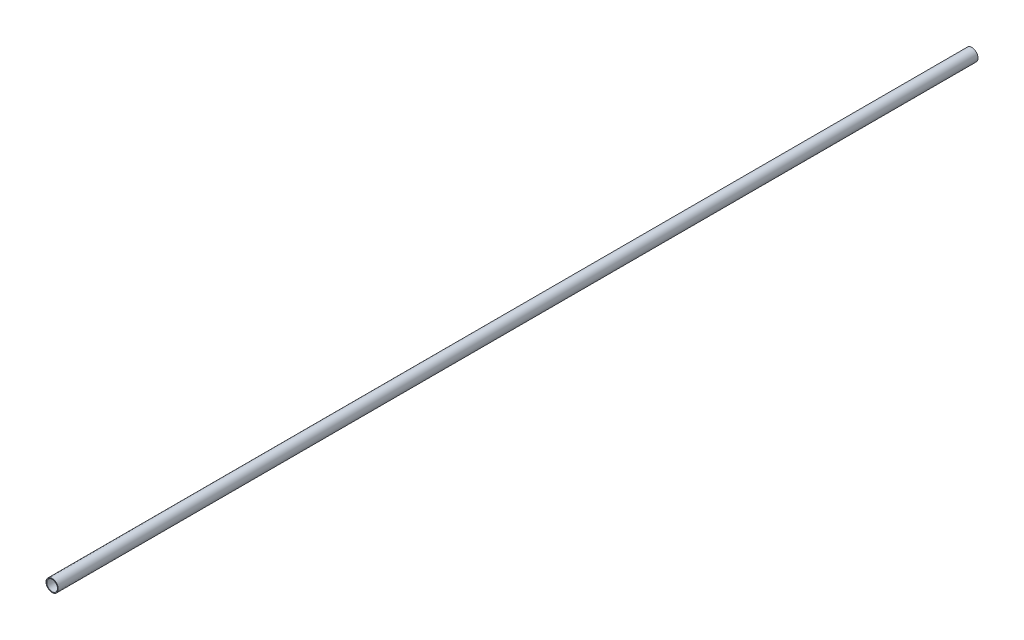
SolidWorks part; units mm, degrees
material "carbon fiber"
ref_plane "Front Plane" through (0, 0, 0) normal (0, 0, 1) x (1, 0, 0)
ref_plane "Top Plane" through (0, 0, 0) normal (0, 1, 0) x (1, 0, 0)
ref_plane "Right Plane" through (0, 0, 0) normal (1, 0, 0) x (0, 0, -1)
sketch "Эскиз1" plane through (0, 0, 0) normal (0, 0, 1) x (1, 0, 0)
  circle A0 centre (0, 0) radius 7
  circle A1 centre (0, 0) radius 8
  dimension "D1" = 1
  dimension "D2" = 14
extrude "Бобышка-Вытянуть1" add sketch "Эскиз1" along normal mid plane 1200
